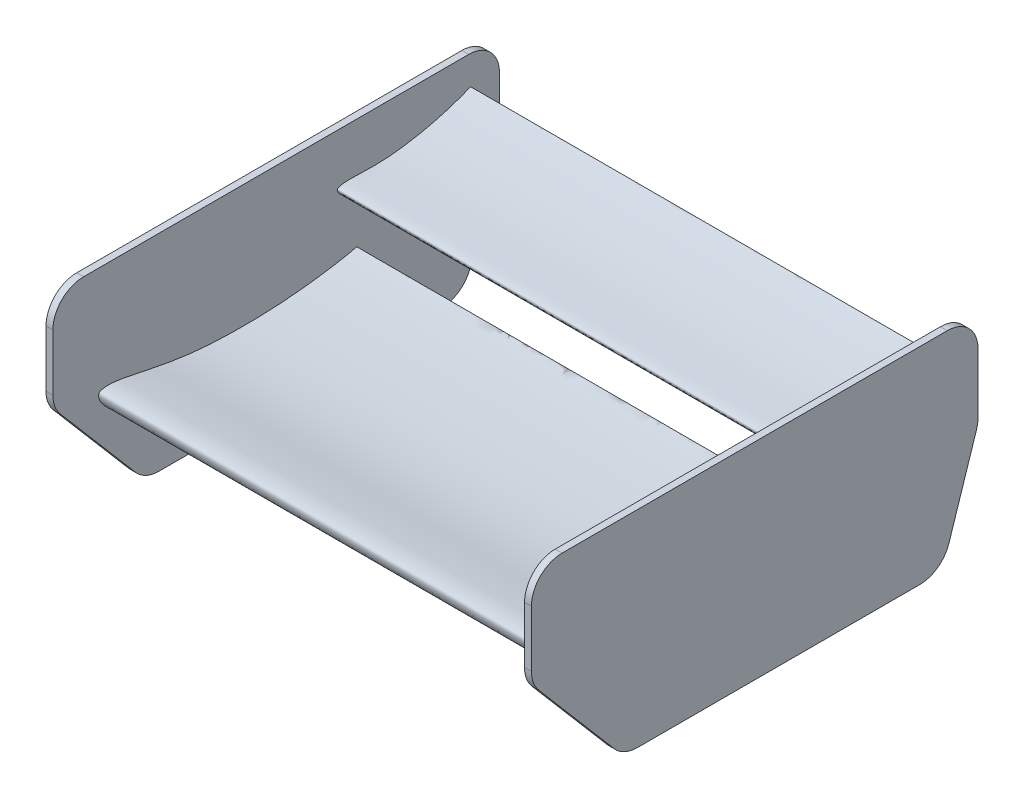
SolidWorks part; units mm, degrees
ref_plane "Front Plane" through (0, 0, 0) normal (0, 0, 1) x (1, 0, 0)
ref_plane "Top Plane" through (0, 0, 0) normal (0, 1, 0) x (1, 0, 0)
ref_plane "Right Plane" through (0, 0, 0) normal (1, 0, 0) x (0, 0, -1)
ref_plane "Soft Top Limit" through (0, 1174.6, 0) normal (0, 1, 0) x (1, 0, 0)
ref_plane "Soft Rear Limit" through (0, 0, -1192.975) normal (0, 0, 1) x (1, 0, 0)
ref_plane "Soft Right Limit" through (-501.65, 0, 0) normal (1, 0, 0) x (0, 0, -1)
ref_plane "Soft Left Limit" through (501.65, 0, 0) normal (1, 0, 0) x (0, 0, -1)
ref_plane "Soft Front Limit" through (0, 0, -165.1) normal (0, 0, 1) x (1, 0, 0)
ref_plane "Slant Limit" through (0, 528.6251, -619.2711) normal (0, -0.6492, 0.7606) x (1, 0, 0)
ref_plane "Bottom" through (0, 476.25, 0) normal (0, 1, 0) x (1, 0, 0)
ref_plane "Midplane" through (0, 0, 0) normal (1, 0, 0) x (0, 0, -1)
curve "Imported Airfoil Curve"
  spline degree 3 poles (0, 2520.0207, 6.126) (0, 2544.889, -1.81) (0, 2521.8965, 7.8839) (0, 2505.3253, 17.7145) (0, 2467.7144, 38.5723) (0, 2424.2142, 62.3813) (0, 2368.0949, 87.8078) (0, 2301.3729, 113.3478) (0, 2223.8362, 140.5377) (0, 2136.6129, 169.2441) (0, 2040.932, 199.097) (0, 1938.2341, 229.6055) (0, 1829.9414, 260.0781) (0, 1717.5266, 289.8586) (0, 1602.4273, 318.1375) (0, 1486.0259, 343.9752) (0, 1369.6902, 366.5754) (0, 1254.3666, 384.7865) (0, 1140.5393, 397.0034) (0, 1028.6357, 403.0127) (0, 919.0585, 402.9406) (0, 812.3986, 397.0375) (0, 709.2785, 385.5985) (0, 610.4299, 369.039) (0, 516.5862, 348.1086) (0, 428.5874, 323.3415) (0, 347.2653, 295.2055) (0, 273.332, 264.2656) (0, 207.4209, 231.0894) (0, 150.0337, 196.3024) (0, 101.596, 160.572) (0, 62.3674, 124.65) (0, 32.4977, 89.3959) (0, 12.0597, 55.6746) (0, 1.683, 26.6201) (0, -0.5567, 6.5526) (0, 0.5894, -3.9947) (0, 1.6947, -9.1451) (0, 2.8711, -12.4915) (0, 3.9449, -14.9776) (0, 4.8993, -16.669) (0, 5.9763, -18.2433) (0, 7.3264, -19.6365) (0, 8.8595, -20.9434) (0, 11.1868, -22.7306) (0, 14.6073, -24.7406) (0, 20.085, -27.4067) (0, 26.8353, -29.9257) (0, 44.6446, -35.1819) (0, 77.8093, -38.8998) (0, 130.2841, -38.2927) (0, 196.3018, -31.4611) (0, 276.2192, -18.4434) (0, 370.8288, 0.8611) (0, 480.7331, 24.811) (0, 605.9792, 50.0099) (0, 745.0759, 74.1542) (0, 895.4497, 95.0846) (0, 1053.6786, 110.004) (0, 1215.6439, 118.3392) (0, 1377.6893, 121.6348) (0, 1537.1174, 120.5125) (0, 1691.5141, 115.2051) (0, 1838.3121, 105.7388) (0, 1975.028, 93.0069) (0, 2099.5942, 78.4581) (0, 2210.5746, 63.1262) (0, 2306.3634, 48.0168) (0, 2387.2069, 33.7158) (0, 2449.0745, 22.0129) (0, 2499.1865, 10.4993) (0, 2520.0207, 6.126) (0, 2544.889, -1.81) (0, 2521.8965, 7.8839) knots -0.016237 -0.007308 -0.001841 0 0.001813 0.006911 0.014576 0.024172 0.035572 0.049013 0.064513 0.081849 0.100772 0.120997 0.142228 0.164173 0.186537 0.209023 0.231367 0.25332 0.274804 0.295858 0.316449 0.336531 0.356033 0.374893 0.39299 0.410197 0.426388 0.441459 0.455334 0.467938 0.479236 0.489204 0.497851 0.505194 0.511308 0.515097 0.516441 0.517273 0.51806 0.518436 0.518797 0.519154 0.519508 0.519887 0.520289 0.52116 0.522116 0.52372 0.525214 0.532575 0.542381 0.554776 0.569931 0.588005 0.609188 0.633329 0.660001 0.688743 0.718873 0.749543 0.780127 0.810209 0.839387 0.867183 0.893104 0.91676 0.937874 0.956199 0.971544 0.983763 0.992692 0.998159 1 1.001813 1.006911 1.014576 periodic
sketch "Airfoils Sketch" plane through (0, 0, 0) normal (1, 0, 0) x (0, 0, -1)
  line L0 (165.1, 1174.6) -> (165.1, 1060.6753) construction
  line L1 (165.1, 1060.6753) -> (663.9798, 476.25) construction
  line L2 (663.9798, 476.25) -> (1192.975, 476.25) construction
  line L3 (1192.975, 476.25) -> (1192.975, 1174.6) construction
  line L4 (1192.975, 1174.6) -> (165.1, 1174.6) construction
  line L5 (509.9361, 1174.6) -> (-509.9361, 1174.6) construction
  line L6 (165.1, 67.0076) -> (165.1, -67.0076) construction
  line L7 (364.7288, 826.8151) -> (873.8134, 230.4351) construction
  line L8 (279.3831, 476.25) -> (-279.3831, 476.25) construction
  line L9 (1192.975, 353.2696) -> (1192.975, -353.2696) construction
  line L10 (364.5896, 868.5327) -> (364.5896, 1023.4673) construction
  line L11 (897.9896, 878.5574) -> (897.9896, 1013.4426) construction
  line L12 (897.9896, 946) -> (364.5896, 946) construction
  line L13 (262.9896, 946) -> (1192.975, 946) construction
  line L14 (848.1751, 1122.607) -> (868.0101, 1010.1175) construction
  line L15 (1123.2328, 1171.6779) -> (1143.263, 1058.0812) construction
  line L16 (1133.2479, 1114.8795) -> (858.0926, 1066.3622) construction
  line L21 (176.2614, 1047.6) -> (1192.975, 1047.6) construction
  spline S0 degree 3 poles (893.7912, 944.7229) (899.0172, 946.3778) (894.1843, 944.3529) (890.6998, 942.2962) (882.7919, 937.9336) (873.6459, 932.9541) (861.8492, 927.6408) (847.826, 922.3086) (831.5308, 916.6349) (813.2009, 910.6474) (793.0943, 904.4229) (771.5139, 898.0641) (748.7586, 891.7155) (725.138, 885.5141) (700.9544, 879.6292) (676.4985, 874.2577) (652.0578, 869.5659) (627.8318, 865.7954) (603.9228, 863.283) (580.4206, 862.0732) (557.4098, 862.1394) (535.0144, 863.4287) (513.3649, 865.8789) (492.6147, 869.4025) (472.9176, 873.8415) (454.4497, 879.0835) (437.3855, 885.0299) (421.8742, 891.5616) (408.0485, 898.5592) (396.0136, 905.8911) (385.8586, 913.417) (377.6374, 920.9787) (371.3813, 928.3959) (367.1052, 935.4868) (364.9396, 941.5929) (364.4786, 945.8081) (364.7242, 948.0225) (364.9587, 949.1035) (365.2073, 949.8057) (365.434, 950.3273) (365.6352, 950.682) (365.8621, 951.0121) (366.1463, 951.304) (366.4688, 951.5778) (366.9584, 951.952) (367.6776, 952.3725) (368.8291, 952.9298) (370.2479, 953.4556) (373.9902, 954.5511) (380.9564, 955.3164) (391.9757, 955.1645) (405.8359, 953.6991) (422.6123, 950.9282) (442.4709, 946.8302) (465.5393, 941.7496) (491.8288, 936.3995) (521.0273, 931.2645) (552.5956, 926.7991) (585.8161, 923.5923) (619.8244, 921.7664) (653.8518, 920.9989) (687.3317, 921.1602) (719.7569, 922.2028) (750.5884, 924.1223) (779.3042, 926.7322) (805.4694, 929.7293) (828.782, 932.8973) (848.9044, 936.0255) (865.8879, 938.991) (878.8853, 941.4197) (889.4141, 943.8142) (893.7912, 944.7229) (899.0172, 946.3778) (894.1843, 944.3529) knots -0.016237 -0.007308 -0.001841 0 0.001813 0.006911 0.014576 0.024172 0.035572 0.049013 0.064513 0.081849 0.100772 0.120997 0.142228 0.164173 0.186537 0.209023 0.231367 0.25332 0.274804 0.295858 0.316449 0.336531 0.356033 0.374893 0.39299 0.410197 0.426388 0.441459 0.455334 0.467938 0.479236 0.489204 0.497851 0.505194 0.511308 0.515097 0.516441 0.517273 0.51806 0.518436 0.518797 0.519154 0.519508 0.519887 0.520289 0.52116 0.522116 0.52372 0.525214 0.532575 0.542381 0.554776 0.569931 0.588005 0.609188 0.633329 0.660001 0.688743 0.718873 0.749543 0.780127 0.810209 0.839387 0.867183 0.893104 0.91676 0.937874 0.956199 0.971544 0.983763 0.992692 0.998159 1 1.001813 1.006911 1.014576 only from (897.9896, 946) to (897.9896, 946)
  spline S1 degree 3 poles (1131.1983, 1113.8389) (1133.7436, 1115.1679) (1131.4347, 1113.6837) (1129.8243, 1112.3058) (1126.1418, 1109.3361) (1121.8768, 1105.9355) (1116.2747, 1102.1216) (1109.5258, 1098.0955) (1101.636, 1093.6865) (1092.7251, 1088.9306) (1082.9193, 1083.8908) (1072.3654, 1078.6477) (1061.2045, 1073.3029) (1049.5838, 1067.9554) (1037.6439, 1062.72) (1025.5169, 1057.7246) (1013.3359, 1053.0813) (1001.1818, 1048.9327) (989.0768, 1045.4619) (977.0633, 1042.7001) (965.1871, 1040.6413) (953.5171, 1039.2693) (942.1263, 1038.564) (931.1018, 1038.4943) (920.5372, 1038.9925) (910.5337, 1040.0168) (901.1902, 1041.5321) (892.5946, 1043.4906) (884.8261, 1045.8428) (877.951, 1048.5303) (872.0279, 1051.4888) (867.0992, 1054.6418) (863.1974, 1057.8989) (860.3465, 1061.1678) (858.674, 1064.1207) (858.0528, 1066.2532) (857.9781, 1067.4178) (858.0007, 1067.9968) (858.0651, 1068.3816) (858.1346, 1068.6713) (858.2061, 1068.8726) (858.2931, 1069.0635) (858.4132, 1069.2399) (858.5547, 1069.4105) (858.7731, 1069.648) (859.1059, 1069.9304) (859.6492, 1070.3226) (860.3333, 1070.7229) (862.1641, 1071.6284) (865.688, 1072.6568) (871.3861, 1073.5807) (878.6693, 1074.0855) (887.5754, 1074.1821) (898.1923, 1073.8745) (910.5543, 1073.3519) (924.6024, 1072.9833) (940.1316, 1072.9902) (956.8223, 1073.5582) (974.2508, 1074.9256) (991.9601, 1077.0771) (1009.5831, 1079.7762) (1026.839, 1082.9048) (1043.4708, 1086.3919) (1059.2007, 1090.1865) (1073.7764, 1094.1448) (1087.0011, 1098.0708) (1098.7388, 1101.8255) (1108.8345, 1105.2695) (1117.3257, 1108.344) (1123.8095, 1110.7791) (1129.023, 1112.972) (1131.1983, 1113.8389) (1133.7436, 1115.1679) (1131.4347, 1113.6837) knots -0.016237 -0.007308 -0.001841 0 0.001813 0.006911 0.014576 0.024172 0.035572 0.049013 0.064513 0.081849 0.100772 0.120997 0.142228 0.164173 0.186537 0.209023 0.231367 0.25332 0.274804 0.295858 0.316449 0.336531 0.356033 0.374893 0.39299 0.410197 0.426388 0.441459 0.455334 0.467938 0.479236 0.489204 0.497851 0.505194 0.511308 0.515097 0.516441 0.517273 0.51806 0.518436 0.518797 0.519154 0.519508 0.519887 0.520289 0.52116 0.522116 0.52372 0.525214 0.532575 0.542381 0.554776 0.569931 0.588005 0.609188 0.633329 0.660001 0.688743 0.718873 0.749543 0.780127 0.810209 0.839387 0.867183 0.893104 0.91676 0.937874 0.956199 0.971544 0.983763 0.992692 0.998159 1 1.001813 1.006911 1.014576 only from (1133.2479, 1114.8795) to (1133.2479, 1114.8795)
  dimension "D1" = 533.4
  dimension "D2" = 228.6
  dimension "D3" = 0
  dimension "D4" = 101.6
  dimension "D5" = 279.4
  dimension "D6" = 59.7205
  dimension "D7" = 10
extrude "Extruded Airfoils" add sketch "Airfoils Sketch" along normal offset from surface (487.45 mm away) 14.2 up to plane "Soft Left Limit"
sketch "Endplate Sketch" plane through (501.65, 0, 0) normal (1, 0, 0) x (0, 0, -1)
  line L6 (333.4477, 1174.6) -> (1129.475, 1174.6)
  line L7 (1192.975, 1174.6) -> (165.1, 1174.6) construction
  line L8 (1192.975, 1111.1) -> (1192.975, 986.6717)
  line L9 (1192.975, 476.25) -> (1192.975, 1174.6) construction
  line L11 (1189.8464, 966.9854) -> (1132.8969, 792.34)
  line L12 (1072.5255, 748.5263) -> (489.1772, 748.5263)
  line L19 (440.8805, 770.7991) -> (285.151, 953.2323)
  line L26 (269.9477, 994.4595) -> (269.9477, 1111.1)
  line L28 (165.1, 1060.6753) -> (663.9798, 476.25) construction
  arc A12 (1129.475, 1174.6) -> (1192.975, 1111.1) centre (1129.475, 1111.1) cw
  arc A13 (1192.975, 986.6717) -> (1189.8464, 966.9854) centre (1129.475, 986.6717) cw
  arc A14 (1132.8969, 792.34) -> (1072.5255, 748.5263) centre (1072.5255, 812.0263) cw
  arc A15 (489.1772, 748.5263) -> (440.8805, 770.7991) centre (489.1772, 812.0263) cw
  arc A16 (285.151, 953.2323) -> (269.9477, 994.4595) centre (333.4477, 994.4595) cw
  arc A17 (333.4477, 1174.6) -> (269.9477, 1111.1) centre (333.4477, 1111.1) ccw
  point P16 (1192.975, 1174.6)
  point P19 (1192.975, 976.5799)
  point P29 (269.9477, 1174.6)
  dimension "D1" = 63.5
extrude "Extruded Endplate" add sketch "Endplate Sketch" against normal up to surface (14.2 mm away)
mirror "Mirror" about plane through (0, 0, 0) normal (1, 0, 0) of bodies 106
